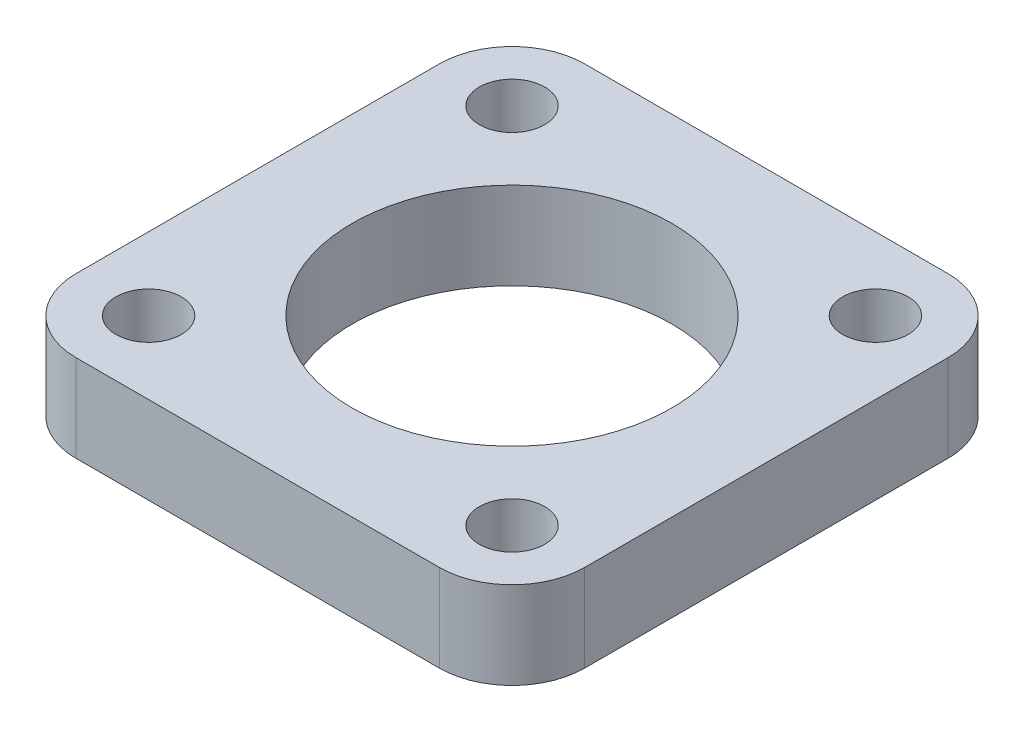
SolidWorks part; units mm, degrees
material "6061-T6 (SS)"
ref_plane "Alzado" through (0, 0, 0) normal (0, 0, 1) x (1, 0, 0)
ref_plane "Planta" through (0, 0, 0) normal (0, 1, 0) x (1, 0, 0)
ref_plane "Vista lateral" through (0, 0, 0) normal (1, 0, 0) x (0, 0, -1)
sketch "Croquis1" plane through (0, 0, 0) normal (0, 1, 0) x (1, 0, 0)
  line L1 (-17.5, -17.5) -> (17.5, -17.5)
  line L2 (-17.5, -17.5) -> (-17.5, 17.5)
  line L3 (-17.5, 17.5) -> (17.5, 17.5)
  line L4 (17.5, -17.5) -> (17.5, 17.5)
  line L5 (-17.5, -17.5) -> (17.5, 17.5) construction
  line L6 (-17.5, 17.5) -> (17.5, -17.5) construction
  circle A0 centre (0, 0) radius 11
  point P0 (0, 0)
  dimension "D2" = 22
  dimension "D1" = 35
extrude "Saliente-Extruir1" add sketch "Croquis1" along normal mid plane 6
hole_wizard "Taladro de margen para M41" positions "Croquis2" profile "Croquis3" hole size "M4" standard "Ansi Metric" end condition up to next
sketch "Croquis2" plane through (0, 3, 0) normal (0, 1, 0) x (1, 0, 0)
  point P0 (12.5, 12.5)
  point P3 (-12.5, 12.5)
  point P6 (-12.5, -12.5)
  point P9 (12.5, -12.5)
sketch "Croquis3" plane through (12.5, 3, -12.5) normal (1, 0, 0) x (0, 0, 1)
  line L0 (0, 0) -> (0, 6)
  line L1 (0, 6) -> (2.25, 6)
  line L2 (2.25, 6) -> (2.25, 0)
  line L5 (2.25, 0) -> (0, 0)
  line L11 (0, -6.35) -> (0, 107.95) construction
  dimension "Diámetro de taladro hasta el siguiente" = 4.5
  dimension "Profundidad de taladro hasta el siguiente" = 6
fillet "Redondeo1" radius 5 4 edges at (17.5, 0, -17.5) (17.5, 0, 17.5) (-17.5, 0, -17.5) (-17.5, 0, 17.5)
